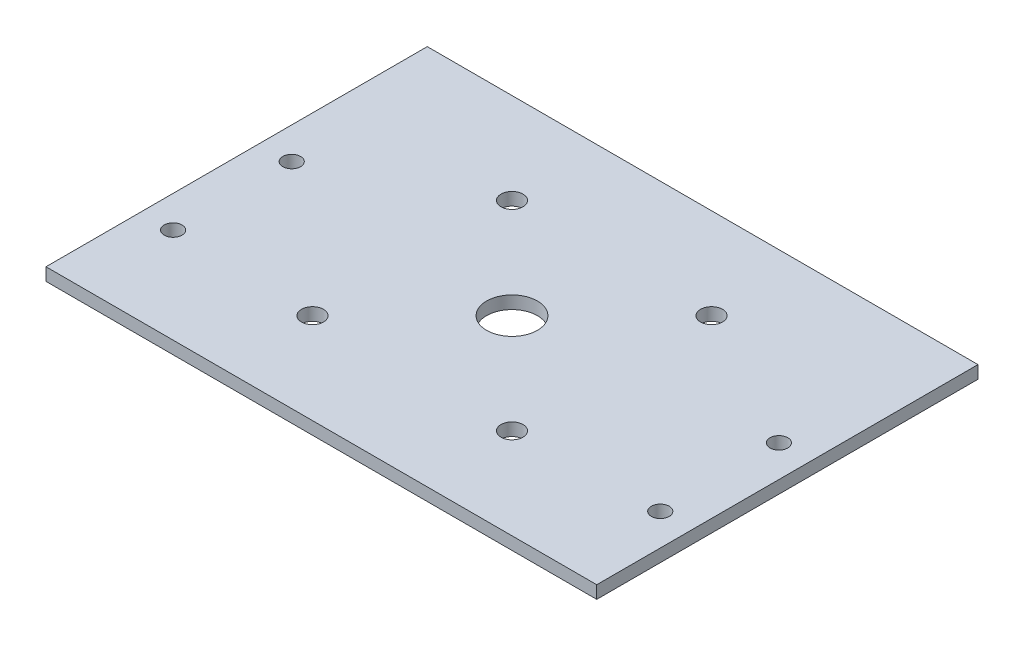
SolidWorks part; units mm, degrees
ref_plane "Front Plane" through (0, 0, 0) normal (0, 0, 1) x (1, 0, 0)
ref_plane "Top Plane" through (0, 0, 0) normal (0, 1, 0) x (1, 0, 0)
ref_plane "Right Plane" through (0, 0, 0) normal (1, 0, 0) x (0, 0, -1)
sketch "Sketch1" plane through (0, 0, 0) normal (0, 1, 0) x (1, 0, 0)
  line L1 (-65, 45) -> (65, 45)
  line L2 (-65, 45) -> (-65, -45)
  line L3 (-65, -45) -> (65, -45)
  line L4 (65, 45) -> (65, -45)
  line L5 (-65, 45) -> (65, -45) construction
  line L6 (-65, -45) -> (65, 45) construction
  point P0 (0, 0)
  dimension "D1" = 130
  dimension "D2" = 90
extrude "Boss-Extrude1" add sketch "Sketch1" along normal blind 3
sketch "Sketch2" plane through (0, 3, 0) normal (0, 1, 0) x (1, 0, 0)
  circle A0 centre (23.55, -23.55) radius 2.6
  circle A1 centre (-23.55, -23.55) radius 2.6
  circle A2 centre (-23.55, 23.55) radius 2.6
  circle A3 centre (23.55, 23.55) radius 2.6
  dimension "D1" = 5.2
extrude "Cut-Extrude1" cut sketch "Sketch2" against normal blind 10
sketch "Sketch3" plane through (0, 0, 0) normal (0, -1, 0) x (1, 0, 0)
  line L0 (-65, 45) -> (65, 45) construction
  line L1 (65, 45) -> (65, -45) construction
  line L2 (-65, -45) -> (-65, 45) construction
  circle A0 centre (57.5, 22.5) radius 2.1
  circle A1 centre (-57.5, 22.5) radius 2.1
  circle A2 centre (-57.5, -5.5) radius 2.1
  circle A3 centre (57.5, -5.5) radius 2.1
  dimension "D1" = 4.2
  dimension "D2" = 22.5
  dimension "D3" = 7.5
  dimension "D4" = 7.5
  dimension "D5" = 4.2
  dimension "D6" = 4.2
extrude "Cut-Extrude2" cut sketch "Sketch3" against normal blind 10
sketch "Sketch4" plane through (0, 0, 0) normal (0, -1, 0) x (1, 0, 0)
  circle A0 centre (0, 0) radius 6
  dimension "D1" = 12
extrude "Cut-Extrude3" cut sketch "Sketch4" against normal blind 10
